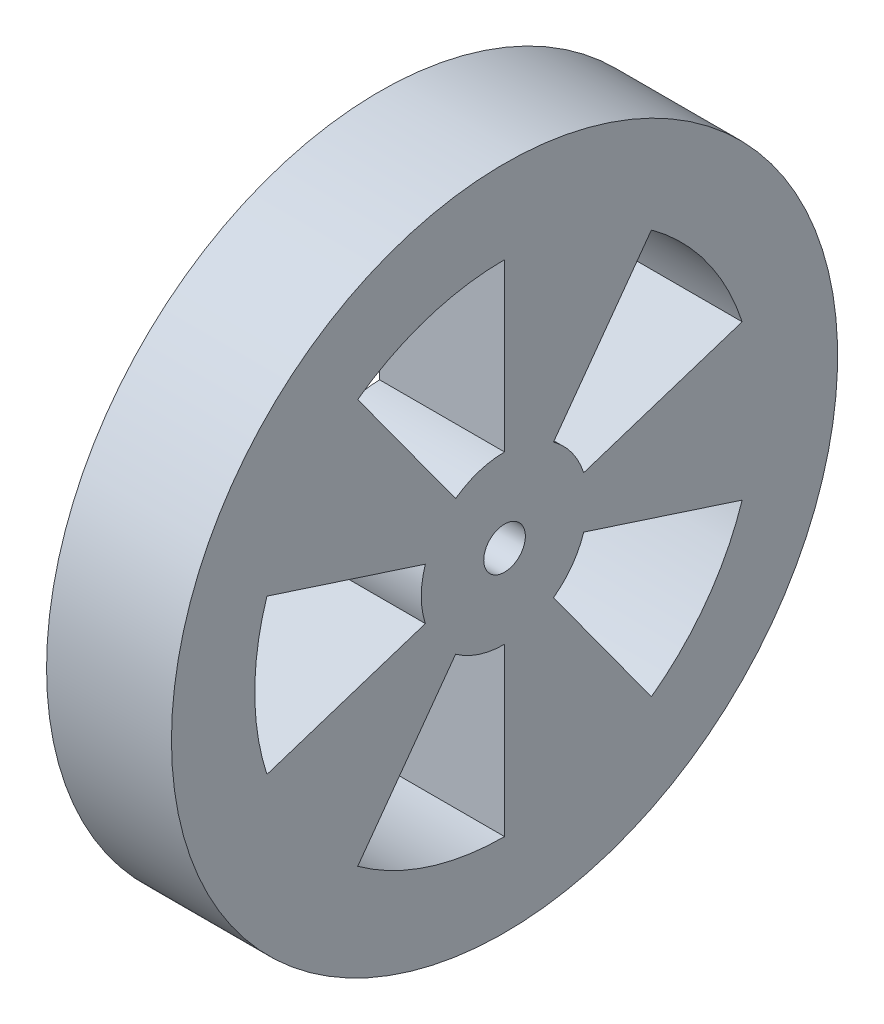
SolidWorks part; units mm, degrees
ref_plane "Front Plane" through (0, 0, 0) normal (0, 0, 1) x (1, 0, 0)
ref_plane "Top Plane" through (0, 0, 0) normal (0, 1, 0) x (1, 0, 0)
ref_plane "Right Plane" through (0, 0, 0) normal (1, 0, 0) x (0, 0, -1)
sketch "Sketch1" plane through (0, 0, 0) normal (1, 0, 0) x (0, 0, -1)
  line L0 (0, 12.7) -> (0, 38.1)
  line L1 (7.4649, 10.2745) -> (22.3946, 30.8235)
  line L2 (12.0784, 3.9245) -> (36.2353, 11.7735)
  line L3 (12.0784, -3.9245) -> (36.2353, -11.7735)
  line L4 (7.4649, -10.2745) -> (22.3946, -30.8235)
  line L5 (0, -12.7) -> (0, -38.1)
  line L6 (-7.4649, -10.2745) -> (-22.3946, -30.8235)
  line L7 (-12.0784, -3.9245) -> (-36.2353, -11.7735)
  line L8 (-12.0784, 3.9245) -> (-36.2353, 11.7735)
  line L9 (-7.4649, 10.2745) -> (-22.3946, 30.8235)
  circle A0 centre (0, 0) radius 50.8
  circle A1 centre (0, 0) radius 38.1
  circle A2 centre (0, 0) radius 12.7
  circle A3 centre (0, 0) radius 3.175
  point P17 (0, 0)
  dimension "D2" = 101.6
  dimension "D3" = 76.2
  dimension "D4" = 25.4
  dimension "D5" = 6.35
  dimension "D1" = 10
extrude "Boss-Extrude1" add sketch "Sketch1" along normal blind 19.05 contours A0 A1 | A2 L1 A1 L0 | A2 L3 A1 L2 | A2 L5 A1 L4 | A2 L7 A1 L6 | A2 L9 A1 L8 | A2
